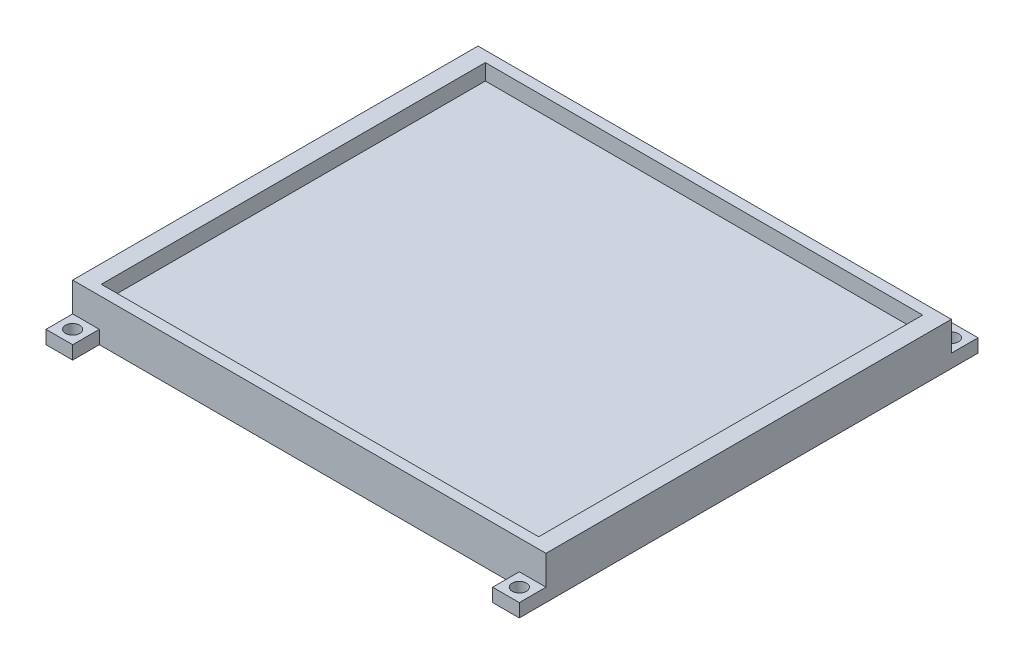
SolidWorks part; units mm, degrees
ref_plane "Front Plane" through (0, 0, 0) normal (0, 0, 1) x (1, 0, 0)
ref_plane "Top Plane" through (0, 0, 0) normal (0, 1, 0) x (1, 0, 0)
ref_plane "Right Plane" through (0, 0, 0) normal (1, 0, 0) x (0, 0, -1)
sketch "Sketch1" plane through (0, 0, 0) normal (0, 1, 0) x (1, 0, 0)
  line L1 (0, 0) -> (112.7, 0)
  line L2 (0, 0) -> (0, 96.52)
  line L3 (0, 96.52) -> (112.7, 96.52)
  line L4 (112.7, 0) -> (112.7, 96.52)
  dimension "D1" = 112.7
  dimension "D2" = 96.52
extrude "Boss-Extrude1" add sketch "Sketch1" along normal blind 10.16
sketch "Sketch2" plane through (0, 10.16, 0) normal (0, 1, 0) x (1, 0, 0)
  line L0 (0, 0) -> (112.7, 0) construction
  line L1 (4.28, 2.54) -> (108.42, 2.54)
  line L2 (4.28, 2.54) -> (4.28, 93.98)
  line L3 (4.28, 93.98) -> (108.42, 93.98)
  line L4 (108.42, 2.54) -> (108.42, 93.98)
  line L6 (0, 96.52) -> (0, 0) construction
  point P6 (56.35, 2.54)
  point P7 (56.35, 0)
  point P8 (4.28, 48.26)
  point P11 (0, 48.26)
  dimension "D1" = 104.14
  dimension "D2" = 91.44
  dimension "D3" = 0
  dimension "D4" = 0
extrude "Cut-Extrude1" cut sketch "Sketch2" against normal blind 3.81
sketch "Sketch3" plane through (0, 0, 0) normal (0, -1, 0) x (1, 0, 0)
  line L1 (112.7, 0) -> (106.35, 0)
  line L2 (112.7, 0) -> (112.7, 6.35)
  line L3 (112.7, 6.35) -> (106.35, 6.35)
  line L4 (106.35, 0) -> (106.35, 6.35)
  line L5 (0, 0) -> (6.35, 0)
  line L6 (0, 0) -> (0, 6.35)
  line L7 (0, 6.35) -> (6.35, 6.35)
  line L8 (6.35, 0) -> (6.35, 6.35)
  line L9 (0, -96.52) -> (6.35, -96.52)
  line L10 (0, -96.52) -> (0, -102.87)
  line L11 (0, -102.87) -> (6.35, -102.87)
  line L12 (6.35, -96.52) -> (6.35, -102.87)
  line L13 (112.7, -96.52) -> (106.35, -96.52)
  line L14 (112.7, -96.52) -> (112.7, -102.87)
  line L15 (112.7, -102.87) -> (106.35, -102.87)
  line L16 (106.35, -96.52) -> (106.35, -102.87)
  circle A0 centre (3.175, 3.175) radius 1.7
  circle A1 centre (109.525, 3.175) radius 1.7
  circle A2 centre (3.175, -99.695) radius 1.7
  circle A3 centre (109.525, -99.695) radius 1.7
  dimension "D9" = 3.4
  dimension "D10" = 3.4
  dimension "D11" = 3.4
  dimension "D12" = 3.4
  dimension "D1" = 6.35
  dimension "D2" = 6.35
  dimension "D3" = 6.35
  dimension "D4" = 6.35
  dimension "D5" = 6.35
  dimension "D6" = 6.35
  dimension "D7" = 6.35
  dimension "D8" = 6.35
extrude "Boss-Extrude2" add sketch "Sketch3" against normal blind 3.175
sketch "Sketch4" plane through (0, 0, 0) normal (0, -1, 0) x (1, 0, 0)
  line L0 (6.35, 0) -> (106.35, 0) construction
  line L1 (6.35, -6.35) -> (106.35, -6.35)
  line L2 (6.35, -6.35) -> (6.35, -90.17)
  line L3 (6.35, -90.17) -> (106.35, -90.17)
  line L4 (106.35, -6.35) -> (106.35, -90.17)
  line L5 (0, -102.87) -> (0, 6.35) construction
  line L6 (112.7, 6.35) -> (112.7, -102.87) construction
  line L7 (106.35, -96.52) -> (6.35, -96.52) construction
  dimension "D1" = 6.35
  dimension "D2" = 6.35
  dimension "D3" = 6.35
  dimension "D4" = 6.35
extrude "Cut-Extrude2" cut sketch "Sketch4" against normal blind 3.81
